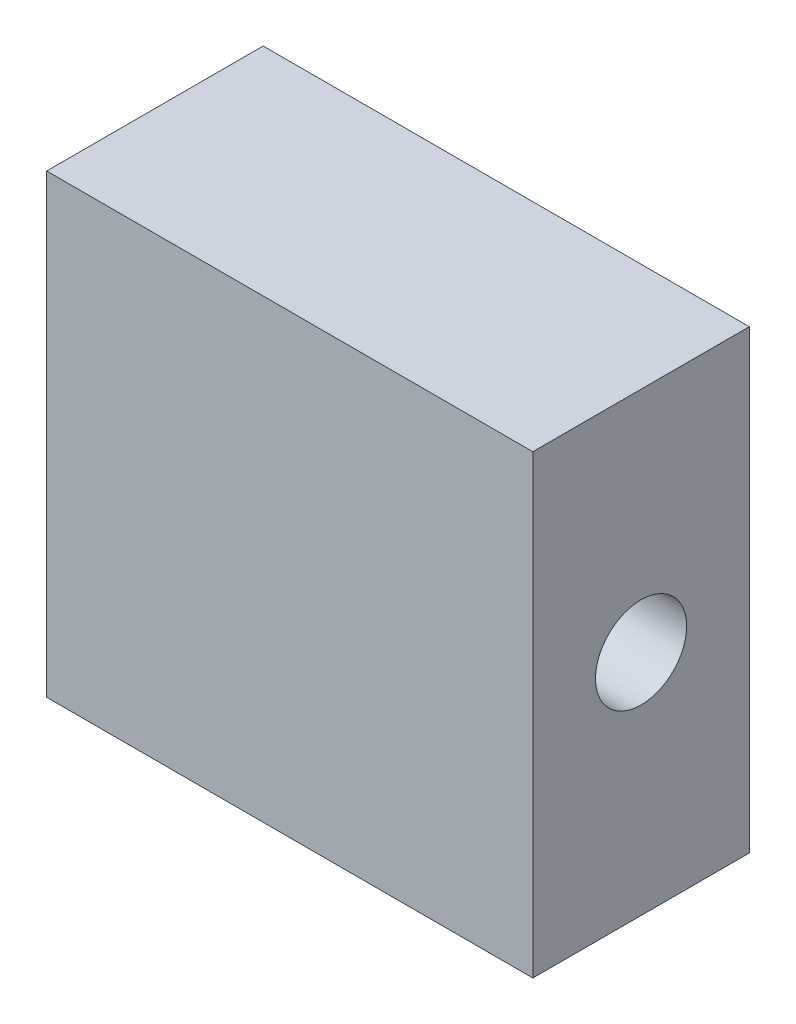
SolidWorks part; units mm, degrees
ref_plane "Front Plane" through (0, 0, 0) normal (0, 0, 1) x (1, 0, 0)
ref_plane "Top Plane" through (0, 0, 0) normal (0, 1, 0) x (1, 0, 0)
ref_plane "Right Plane" through (0, 0, 0) normal (1, 0, 0) x (0, 0, -1)
sketch "Sketch1" plane through (0, 0, 0) normal (0, 0, 1) x (1, 0, 0)
  line L1 (-16, -15) -> (16, -15)
  line L2 (-16, -15) -> (-16, 15)
  line L3 (-16, 15) -> (16, 15)
  line L4 (16, -15) -> (16, 15)
  line L5 (-16, -15) -> (16, 15) construction
  line L6 (-16, 15) -> (16, -15) construction
  point P0 (0, 0)
  point P5 (-10.6667, 10)
  point P6 (-10.6667, -10)
  point P8 (9.3333, -10)
  point P9 (0, 0)
  point P10 (9.3333, 10)
  point P11 (10.6667, -10)
  point P12 (7.6489, -10)
  dimension "D1" = 32
  dimension "D2" = 30
  dimension "D3" = 20
  dimension "D4" = 20
extrude "Boss-Extrude1" add sketch "Sketch1" along normal mid plane 14.25
hole_wizard "M3x0.5 Tapped Hole1" positions "Sketch2" profile "Sketch4" tap size "M3x0.5" standard "ANSI Metric"
sketch "Sketch2" plane through (0, 0, -7.125) normal (0, 0, -1) x (-1, 0, 0)
  point P0 (-9.3333, 10)
  point P3 (10.6667, 10)
  point P6 (10.6667, -10)
  point P9 (-9.3333, -10)
sketch "Sketch4" plane through (9.3333, 10, -7.125) normal (1, 0, 0) x (0, 1, 0)
  line L0 (0, 0) -> (0, 8.2511)
  line L1 (0, 8.2511) -> (1.25, 7.5)
  line L2 (1.25, 7.5) -> (1.25, 0)
  line L5 (1.25, 0) -> (0, 0)
  line L10 (0, 8.2511) -> (-1.25, 7.5) construction
  line L11 (0, -6.35) -> (0, 107.95) construction
  dimension "Tap Drill Dia." = 2.5
  dimension "Tap Drill Depth" = 7.5
  dimension "Drill Angle" = 118
hole_wizard "M6x1.0 Tapped Hole1" positions "Sketch6" profile "Sketch7" tap size "M6x1.0" standard "ANSI Metric" end condition through all
sketch "Sketch6" plane through (16, 0, 0) normal (1, 0, 0) x (0, 0, -1)
  point P0 (0, 0)
sketch "Sketch7" plane through (16, 0, 0) normal (0, 1, 0) x (0, 0, -1)
  line L0 (0, 0) -> (0, 32)
  line L1 (0, 32) -> (3, 32)
  line L2 (3, 32) -> (3, 0)
  line L5 (3, 0) -> (0, 0)
  line L11 (0, -6.35) -> (0, 107.95) construction
  dimension "Thread Major Dia." = 6
  dimension "Thru Tap Drill Depth" = 32
